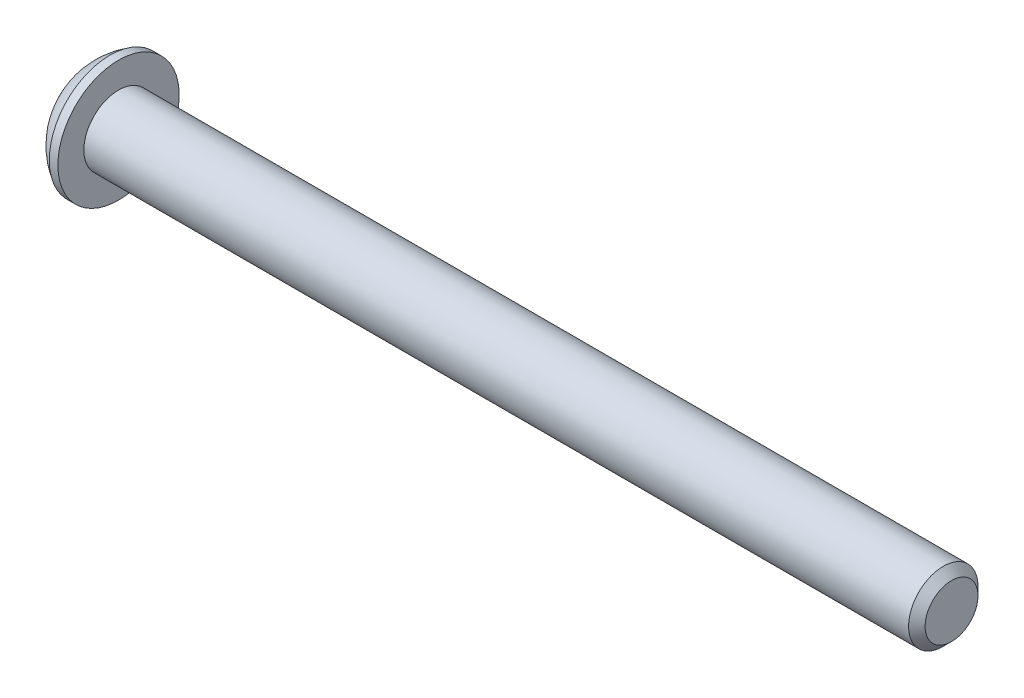
SolidWorks part; units mm, degrees
ref_plane "Plane1" through (0, 0, 0) normal (0, 0, 1) x (1, 0, 0)
ref_plane "Plane2" through (0, 0, 0) normal (0, 1, 0) x (1, 0, 0)
ref_plane "Plane3" through (0, 0, 0) normal (1, 0, 0) x (0, 0, -1)
other "Configuration Table"
sketch "BodySke" plane through (0, 0, 0) normal (0, 0, 1) x (1, 0, 0)
  line L0 (79.5528, 0) -> (79.5528, 2.4193)
  line L1 (78.7972, 3.175) -> (3.3528, 3.175)
  line L2 (3.3528, 3.175) -> (3.3528, 5.5499)
  line L3 (3.3528, 5.5499) -> (2.5654, 5.5499)
  line L4 (0, 0) -> (101.6, 0) construction
  line L5 (3.3528, -5.5499) -> (2.5654, -5.5499) construction
  line L6 (55.6768, -3.175) -> (3.3528, -3.175) construction
  line L7 (79.5528, 0) -> (0, 0)
  line L8 (0, 2.775) -> (0, -2.775) construction
  line L9 (0, 0) -> (0, 2.775)
  line L10 (79.5528, 2.4193) -> (78.7972, 3.175)
  line L11 (79.5528, -2.4193) -> (78.7972, -3.175) construction
  line L12 (4.6228, 9.525) -> (4.6228, -3.175) construction
  line L13 (16.0528, 9.525) -> (16.0528, -3.175) construction
  arc A1 (0, 2.775) -> (2.5654, 5.5499) centre (5.7851, 0) cw
  dimension "Diameter" = 6.35
  dimension "Length" = 76.2
  dimension "Head_dia" = 11.0998
  dimension "D1" = 5.5499
  dimension "Head_ht" = 3.3528
  dimension "Head_side_ht" = 0.7874
  dimension "Minor_dia" = 4.8387
  dimension "Body_ch_ang" = 45
  dimension "Advance" = 1.27
  dimension "Thread_nom" = 63.5
revolve "BaseBody" add sketch "BodySke" angle 360 about L4
cosmetic thread "ThreadCosmetic" [suppressed] parameters "Thread_length"=63.5, "Thread_minor"=4.8387
sketch "Sketch2" plane through (0, 0, 0) normal (0, 0, 1) x (1, 0, 0)
  line L0 (0, 1.9812) -> (2.2098, 1.9812)
  line L1 (2.2098, 1.9812) -> (3.3536, 0)
  line L3 (3.3536, 0) -> (0, 0)
  line L4 (0, 0) -> (0, 1.9812)
  line L5 (0, -1.9812) -> (2.2098, -1.9812) construction
  line L6 (0, 0) -> (47.625, 0) construction
  dimension "D2" = 60
  dimension "PreBroach_depth" = 2.2098
  dimension "PreBroach_dia" = 3.9624
revolve "PreBroach" cut sketch "Sketch2" angle 360 about L6
sketch "Sketch3" plane through (0, 0, 0) normal (1, 0, 0) x (0, 0, -1)
  line L0 (-1.9812, -1.1438) -> (-1.9812, 1.1438)
  line L1 (-1.9812, 1.1438) -> (0, 2.2877)
  line L2 (0, 2.2877) -> (1.9812, 1.1438)
  line L3 (1.9812, 1.1438) -> (1.9812, -1.1438)
  line L4 (1.9812, -1.1438) -> (0, -2.2877)
  line L5 (0, -2.2877) -> (-1.9812, -1.1438)
  dimension "Hex_size" = 3.9624
  dimension "D3" = 3.9624
  dimension "D1" = 1.9812
  dimension "D2" = 1.9812
extrude "Hex" cut sketch "Sketch3" along normal blind 2.2098
sketch "Sketch4" plane through (0, 9.525, 0) normal (1, 0, 0) x (0, 0, -1)
  line L0 (0, -9.525) -> (2.3876, -9.525)
  line L1 (0, -9.525) -> (6.1484, -5.9752) construction
  line L2 (0, -9.525) -> (1.1938, -7.4573)
  line L3 (1.9883, -8.949) -> (2.2704, -8.7861)
  line L4 (1.493, -8.0911) -> (1.7751, -7.9282)
  arc A0 (1.9883, -8.949) -> (1.493, -8.0911) centre (0, -9.525) ccw
  arc A1 (2.3876, -9.525) -> (2.2704, -8.7861) centre (0, -9.525) ccw
  arc A2 (1.1938, -7.4573) -> (1.7751, -7.9282) centre (0, -9.525) cw
  dimension "Spline_n_dim" = 4.1402
  dimension "Spline_m_dim" = 4.7752
  dimension "D1" = 30
  dimension "D2" = 60
  dimension "Spline_p_dim" = 0.9906
  dimension "D3" = 0.4953
extrude "Spline" [suppressed] cut sketch "Sketch4" along normal blind 2.2098
pattern_circular "CirPattern1" [suppressed] count 6 every 60 about axis through (0, 0, 0) along (1, 0, 0)
sketch "ThdSchSke" plane through (0, 0, 0) normal (0, 0, 1) x (1, 0, 0)
  line L0 (16.0528, -2.4193) -> (15.5237, -3.175)
  line L1 (16.0528, -2.4193) -> (16.5819, -3.175)
  line L2 (16.5819, -3.175) -> (16.5819, -3.9687)
  line L3 (-3.175, 0) -> (5.1513, 0) construction
  line L5 (16.5819, -3.9687) -> (15.5237, -3.9687)
  line L6 (15.5237, -3.9687) -> (15.5237, -3.175)
  dimension "Diameter" = 6.35
  dimension "Thread_minor" = 4.8387
  dimension "SideAngle" = 55
  dimension "VeeAngle" = 70
  dimension "Overcut" = 7.9375
  dimension "Start" = 16.0528
revolve "ThreadSchematic" [suppressed] cut sketch "ThdSchSke" angle 360 about L3
pattern_linear "ThdSchPat" [suppressed]
equation "\"D1@BodySke\" = \"Head_dia@BodySke\" * .5"
equation "\"Thread_minor@ThreadCosmetic\" = \"Minor_dia@BodySke\""
equation "\"D1@Sketch3\" = \"Hex_size@Sketch3\" / 2"
equation "\"D2@Sketch3\" = \"D1@Sketch3\""
equation "\"D3@Sketch3\" = \"Hex_size@Sketch3\""
equation "\"D3@Sketch4\" = \"Spline_p_dim@Sketch4\" / 2"
equation "\"D1@Sketch4\" = \"D2@Sketch4\" / 2"
equation "\"Thread_length@ThreadCosmetic\" = ((sgn( (\"Length@BodySke\" - \"Advance@BodySke\" ) - \"Thread_nom@BodySke\" )-1)*( (\"Length@BodySke\" - \"Advance@BodySke\" ) - \"Thread_nom@BodySke\" ))/-2+ \"Thread_nom@BodySke\""
equation "\"Thread_minor@ThdSchSke\" = \"Minor_dia@BodySke\""
equation "\"Diameter@ThdSchSke\" = \"Diameter@BodySke\""
equation "\"Overcut@ThdSchSke\" = \"Diameter@BodySke\" * 1.25"
equation "\"Start@ThdSchSke\" = \"Head_ht@BodySke\" + \"Length@BodySke\" - \"Thread_length@ThreadCosmetic\"  '---Non-countersunk---"
equation "\"Num_threads@ThdSchPat\" = int( \"Thread_length@ThreadCosmetic\" / \"Advance@BodySke\" + 0.999 )  + 1"
equation "\"Advance@ThdSchPat\" = \"Thread_length@ThreadCosmetic\" /  (\"Num_threads@ThdSchPat\" - 1) 'relax it"
equation "\"Num_threads@ThdSchPat\" = \"Num_threads@ThdSchPat\" - sgn( \"Num_threads@ThdSchPat\" - 1) '---chamfered tips only---"
